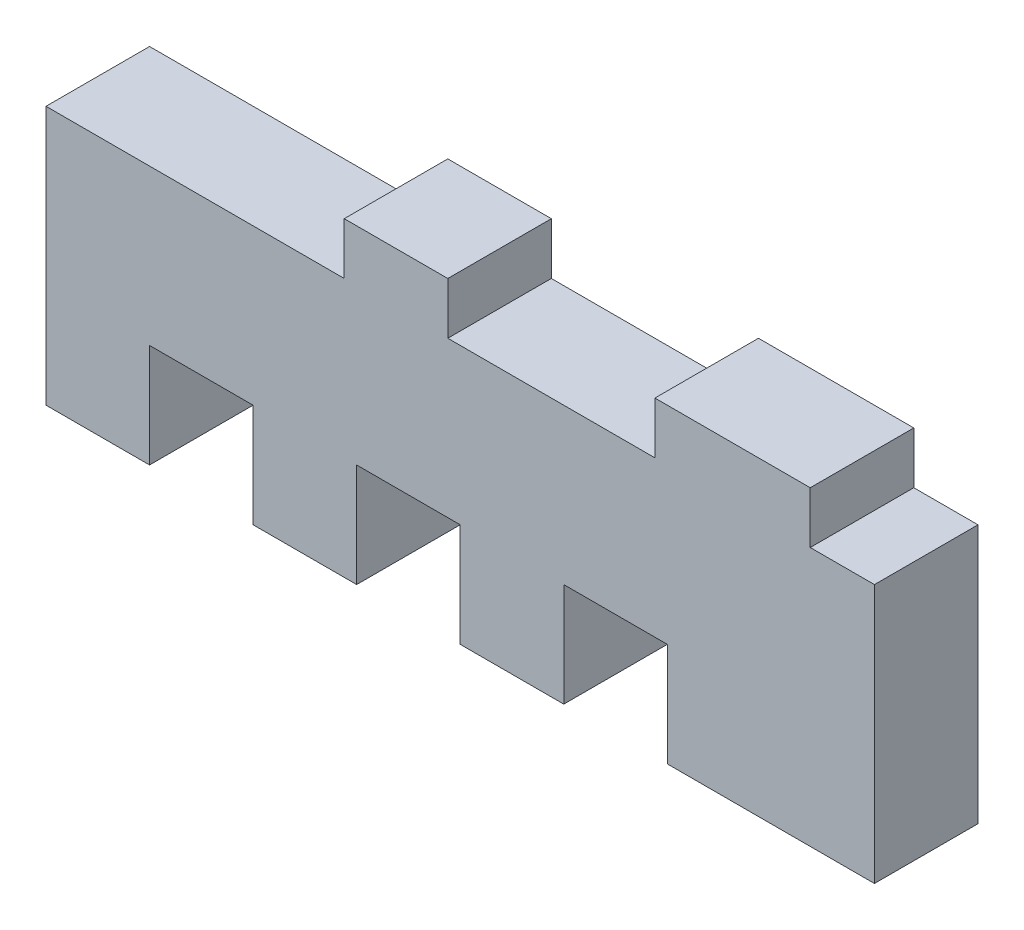
SolidWorks part; units mm, degrees
material "Balsa"
ref_plane "Front Plane" through (0, 0, 0) normal (0, 0, 1) x (1, 0, 0)
ref_plane "Top Plane" through (0, 0, 0) normal (0, 1, 0) x (1, 0, 0)
ref_plane "Right Plane" through (0, 0, 0) normal (1, 0, 0) x (0, 0, -1)
sketch "Sketch1" plane through (0, 0, 0) normal (0, 0, 1) x (1, 0, 0)
  line L0 (0, 0) -> (36.576, 0)
  line L1 (36.576, 0) -> (36.576, 6.35)
  line L2 (36.576, 6.35) -> (49.276, 6.35)
  line L3 (49.276, 6.35) -> (49.276, 0)
  line L4 (49.276, 0) -> (74.676, 0)
  line L5 (74.676, 0) -> (74.676, 6.35)
  line L6 (74.676, 6.35) -> (93.726, 6.35)
  line L7 (93.726, 6.35) -> (93.726, 0)
  line L8 (93.726, 0) -> (101.6, 0)
  line L9 (0, 0) -> (0, -31.75)
  line L10 (101.6, 0) -> (101.6, -31.75)
  line L11 (0, -31.75) -> (12.7, -31.75)
  line L12 (12.7, -31.75) -> (12.7, -19.05)
  line L13 (12.7, -19.05) -> (25.4, -19.05)
  line L14 (25.4, -19.05) -> (25.4, -31.75)
  line L15 (25.4, -31.75) -> (38.1, -31.75)
  line L16 (38.1, -31.75) -> (38.1, -19.05)
  line L17 (38.1, -19.05) -> (50.8, -19.05)
  line L18 (50.8, -19.05) -> (50.8, -31.75)
  line L20 (50.8, -31.75) -> (63.5, -31.75)
  line L21 (63.5, -31.75) -> (63.5, -19.05)
  line L22 (63.5, -19.05) -> (76.2, -19.05)
  line L23 (76.2, -19.05) -> (76.2, -31.75)
  line L24 (76.2, -31.75) -> (101.6, -31.75)
  dimension "D1" = 36.576
  dimension "D2" = 6.35
  dimension "D3" = 6.35
  dimension "D4" = 12.7
  dimension "D5" = 25.4
  dimension "D6" = 19.05
  dimension "D7" = 101.6
  dimension "D8" = 31.75
  dimension "D9" = 31.75
  dimension "D10" = 12.7
  dimension "D11" = 12.7
  dimension "D12" = 12.7
  dimension "D13" = 12.7
  dimension "D14" = 12.7
  dimension "D15" = 12.7
  dimension "D16" = 12.7
  dimension "D17" = 12.7
  dimension "D18" = 12.7
  dimension "D19" = 12.7
  dimension "D20" = 12.7
extrude "Boss-Extrude1" add sketch "Sketch1" along normal blind 12.7
